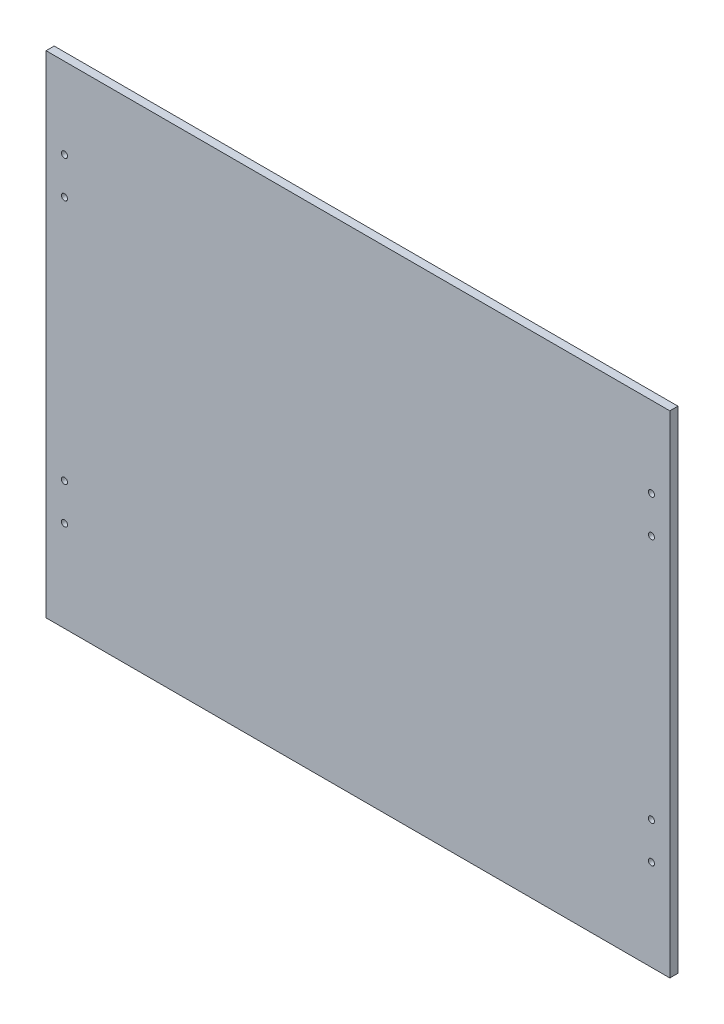
SolidWorks part; units mm, degrees
ref_plane "Front Plane" through (0, 0, 0) normal (0, 0, 1) x (1, 0, 0)
ref_plane "Top Plane" through (0, 0, 0) normal (0, 1, 0) x (1, 0, 0)
ref_plane "Right Plane" through (0, 0, 0) normal (1, 0, 0) x (0, 0, -1)
sketch "Sketch1" plane through (0, 0, 0) normal (0, 0, 1) x (1, 0, 0)
  line L1 (-115.4545, 117.9286) -> (138.5455, 117.9286)
  line L2 (-115.4545, 117.9286) -> (-115.4545, -82.0714)
  line L3 (-115.4545, -82.0714) -> (138.5455, -82.0714)
  line L4 (138.5455, 117.9286) -> (138.5455, -82.0714)
  circle A0 centre (-107.9545, 85.0286) radius 1.25
  circle A1 centre (-107.9545, 70.0286) radius 1.25
  circle A2 centre (131.0455, 85.0286) radius 1.25
  circle A3 centre (131.0455, 70.0286) radius 1.25
  circle A4 centre (-107.9545, -29.9714) radius 1.25
  circle A5 centre (131.0455, -29.9714) radius 1.25
  circle A6 centre (-107.9545, -44.9714) radius 1.25
  circle A7 centre (131.0455, -44.9714) radius 1.25
  dimension "D3" = 7.5
  dimension "D7" = 7.5
  dimension "D9" = 100
  dimension "D12" = 15
  dimension "D1" = 254
  dimension "D2" = 200
  dimension "D4" = 32.9
  dimension "D5" = 15
  dimension "D6" = 7.5
  dimension "D8" = 7.5
  dimension "D10" = 100
  dimension "D11" = 239
extrude "Boss-Extrude1" add sketch "Sketch1" along normal blind 3.3
